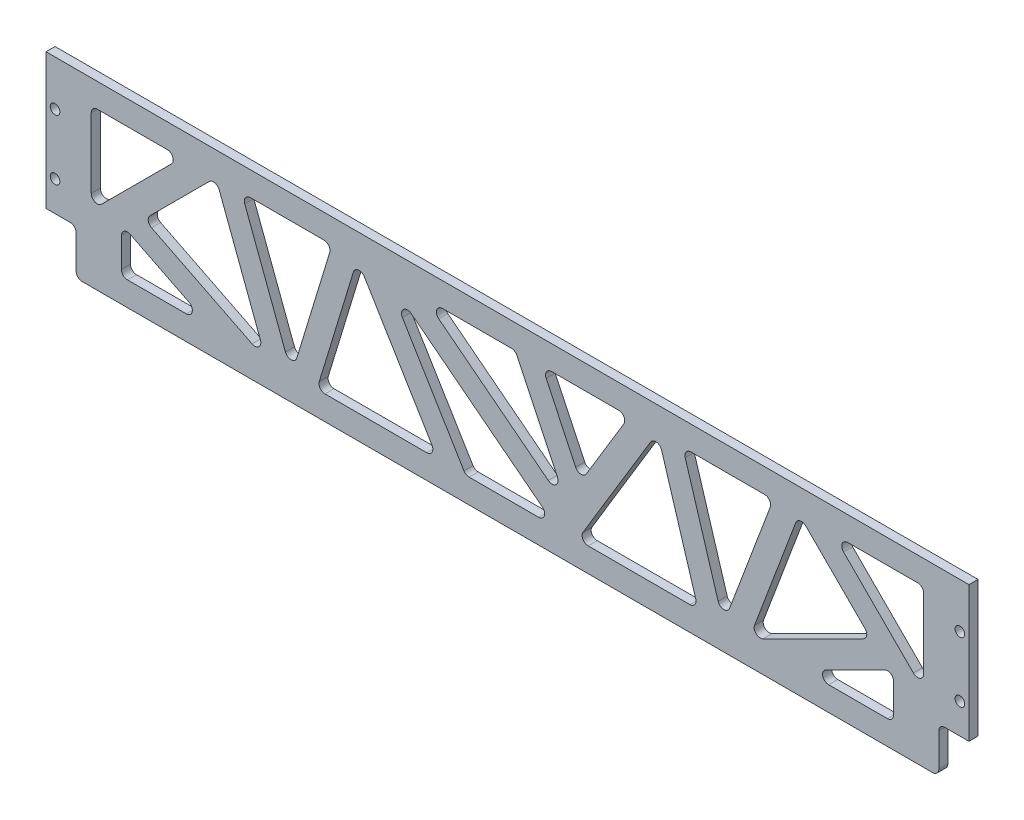
SolidWorks part; units mm, degrees
material "环氧树脂FR-4"
ref_plane "前视基准面" through (0, 0, 0) normal (0, 0, 1) x (1, 0, 0)
ref_plane "上视基准面" through (0, 0, 0) normal (0, 1, 0) x (1, 0, 0)
ref_plane "右视基准面" through (0, 0, 0) normal (1, 0, 0) x (0, 0, -1)
sketch "草图1" plane through (0, 0, 0) normal (0, 0, 1) x (1, 0, 0)
  line L1 (-153, 30) -> (153, 30)
  line L2 (-153, 30) -> (-153, -30)
  line L3 (-153, -30) -> (153, -30)
  line L4 (153, 30) -> (153, -30)
  line L5 (-153, 30) -> (153, -30) construction
  line L6 (-153, -30) -> (153, 30) construction
  point P0 (0, 0)
  dimension "D1" = 60
  dimension "D2" = 306
extrude "凸台-拉伸1" add sketch "草图1" along normal blind 3
sketch "草图2" plane through (0, 0, 3) normal (0, 0, 1) x (1, 0, 0)
  line L0 (-153, 30) -> (-153, -30) construction
  line L1 (153, 30) -> (-153, 30) construction
  line L2 (0, -55) -> (0, 55) construction
  point P0 (-150, 15)
  point P1 (-150, -5)
  point P8 (150, -5)
  point P9 (150, 15)
  dimension "D1" = 3
  dimension "D2" = 15
  dimension "D3" = 3
  dimension "D4" = 20
hole_wizard "Ø3.2 (3.2) 直径孔1" positions "3D草图1" profile "草图3" hole size "Ø3.2" standard "GB" end condition through all
sketch3d "3D草图1"
  point P0 (-150, 15, 3)
  point P3 (-150, -5, 3)
  point P6 (150, 15, 3)
  point P9 (150, -5, 3)
sketch "草图3" plane through (-150, 15, 3) normal (1, 0, 0) x (0, -1, 0)
  line L0 (0, 0) -> (0, 3)
  line L1 (0, 3) -> (1.6, 3)
  line L2 (1.6, 3) -> (1.6, 0)
  line L5 (1.6, 0) -> (0, 0)
  line L11 (0, -6.35) -> (0, 107.95) construction
  dimension "通孔孔直径" = 3.2
  dimension "通孔孔深度" = 3
sketch "草图4" plane through (0, 0, 3) normal (0, 0, 1) x (1, 0, 0)
  line L0 (-138, 22) -> (-138, -8)
  line L1 (-153, -30) -> (-143, -30)
  line L2 (-153, -30) -> (-153, -15)
  line L3 (-153, -15) -> (-143, -15)
  line L4 (-143, -30) -> (-143, -15)
  line L5 (-138, -8) -> (-108, 22)
  line L6 (-108, 22) -> (-138, 22)
  line L7 (-153, 30) -> (-153, -30) construction
  line L8 (153, 30) -> (-153, 30) construction
  line L9 (-128, -7) -> (-128, -22)
  line L10 (-128, -22) -> (-98, -22)
  line L11 (-98, -22) -> (-128, -7)
  line L12 (-153, -30) -> (153, -30) construction
  line L13 (-120.4947, -1.8084) -> (-80.1115, -22)
  line L14 (-80.1115, -22) -> (-96.6863, 22)
  line L15 (-96.6863, 22) -> (-120.4947, -1.8084)
  line L16 (-88.1375, 22) -> (-58.1375, 22)
  line L17 (-58.1375, 22) -> (-71.5627, -22)
  line L18 (-71.5627, -22) -> (-88.1375, 22)
  line L19 (-49.7734, 22) -> (-63.1986, -22)
  line L20 (-63.1986, -22) -> (-23.1986, -22)
  line L21 (-23.1986, -22) -> (-49.7734, 22)
  line L22 (0, -55) -> (0, 55) construction
  line L23 (23.1986, -22) -> (49.7734, 22)
  line L24 (63.1986, -22) -> (23.1986, -22)
  line L25 (49.7734, 22) -> (63.1986, -22)
  line L26 (71.5627, -22) -> (88.1375, 22)
  line L27 (58.1375, 22) -> (71.5627, -22)
  line L28 (88.1375, 22) -> (58.1375, 22)
  line L29 (96.6863, 22) -> (120.4947, -1.8084)
  line L30 (80.1115, -22) -> (96.6863, 22)
  line L31 (120.4947, -1.8084) -> (80.1115, -22)
  line L32 (98, -22) -> (128, -7)
  line L33 (128, -22) -> (98, -22)
  line L34 (128, -7) -> (128, -22)
  line L35 (108, 22) -> (138, 22)
  line L36 (138, -8) -> (108, 22)
  line L37 (143, -30) -> (143, -15)
  line L38 (153, -15) -> (143, -15)
  line L39 (153, -30) -> (153, -15)
  line L40 (153, -30) -> (143, -30)
  line L41 (138, 22) -> (138, -8)
  line L42 (-40.4275, 22) -> (-13.8526, -22)
  line L43 (-13.8526, -22) -> (16.1474, -22)
  line L44 (16.1474, -22) -> (-40.4275, 22)
  line L45 (-27.3964, 22) -> (20.1779, -15)
  line L46 (20.1779, -15) -> (2.6036, 22)
  line L47 (2.6036, 22) -> (-27.3964, 22)
  line L48 (11.4602, 22) -> (24.2122, -4.8476)
  line L49 (24.2122, -4.8476) -> (40.4275, 22)
  line L50 (40.4275, 22) -> (11.4602, 22)
  dimension "D1" = 10
  dimension "D2" = 15
  dimension "D3" = 15
  dimension "D4" = 8
  dimension "D5" = 30
  dimension "D6" = 30
  dimension "D7" = 15
  dimension "D8" = 30
  dimension "D9" = 15
  dimension "D10" = 8
  dimension "D11" = 8
  dimension "D12" = 8
  dimension "D13" = 8
  dimension "D14" = 8
  dimension "D15" = 8
  dimension "D16" = 30
  dimension "D17" = 8
  dimension "D18" = 8
  dimension "D19" = 8
  dimension "D20" = 8
  dimension "D21" = 40
  dimension "D22" = 8
  dimension "D23" = 8
  dimension "D24" = 30
  dimension "D25" = 8
  dimension "D26" = 8
  dimension "D27" = 30
  dimension "D28" = 15
  dimension "D29" = 8
  dimension "D30" = 8
  dimension "D31" = 8
extrude "切除-拉伸1" cut sketch "草图4" against normal through all
fillet "圆角1" radius 2 39 edges at (138, 22, 1.5) (108, 22, 1.5) (138, -8, 1.5) (128, -7, 1.5) (128, -22, 1.5) (98, -22, 1.5) (120.4947, -1.8084, 1.5) (96.6863, 22, 1.5) (80.1115, -22, 1.5) (71.5627, -22, 1.5) (88.1375, 22, 1.5) (58.1375, 22, 1.5) (49.7734, 22, 1.5) (63.1986, -22, 1.5) (23.1986, -22, 1.5) (2.6036, 22, 1.5) (20.1779, -15, 1.5) (-27.3964, 22, 1.5) (16.1474, -22, 1.5) (-40.4275, 22, 1.5) (-13.8526, -22, 1.5) (-23.1986, -22, 1.5) (-63.1986, -22, 1.5) (-49.7734, 22, 1.5) (-58.1375, 22, 1.5) (-71.5627, -22, 1.5) (-88.1375, 22, 1.5) (-80.1115, -22, 1.5) (-96.6863, 22, 1.5) (-120.4947, -1.8084, 1.5) (-98, -22, 1.5) (-128, -22, 1.5) (-128, -7, 1.5) (-138, -8, 1.5) (-108, 22, 1.5) (-138, 22, 1.5) (40.4275, 22, 1.5) (24.2122, -4.8476, 1.5) (11.4602, 22, 1.5)
fillet "圆角2" radius 2 4 edges at (-143, -30, 1.5) (143, -30, 1.5) (143, -15, 1.5) (-143, -15, 1.5)
